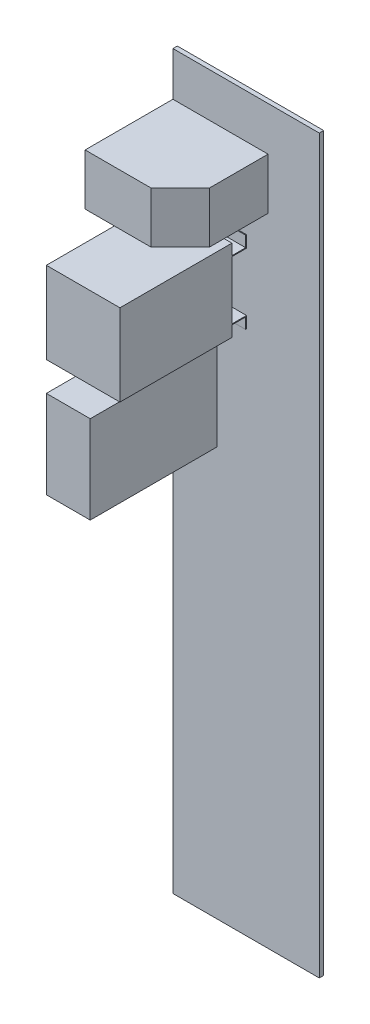
SolidWorks part; units mm, degrees
ref_plane "前视基准面" through (0, 0, 0) normal (0, 0, 1) x (1, 0, 0)
ref_plane "上视基准面" through (0, 0, 0) normal (0, 1, 0) x (1, 0, 0)
ref_plane "右视基准面" through (0, 0, 0) normal (1, 0, 0) x (0, 0, -1)
sketch "草图1" plane through (0, 0, 0) normal (0, 0, 1) x (1, 0, 0)
  line L1 (-251.5, 279) -> (251.5, 279)
  line L2 (-251.5, 279) -> (-251.5, -279)
  line L3 (-251.5, -279) -> (251.5, -279)
  line L4 (251.5, 279) -> (251.5, -279)
  line L5 (-251.5, 279) -> (251.5, -279) construction
  line L6 (-251.5, -279) -> (251.5, 279) construction
  point P0 (0, 0)
  dimension "D1" = 558
  dimension "D2" = 503
extrude "凸台-拉伸1" add sketch "草图1" along normal blind 865
sketch "草图2" plane through (251.5, 0, 0) normal (1, 0, 0) x (0, 0, -1)
  line L0 (0, -279) -> (0, 279) construction
  line L1 (100, 199) -> (-100, 199)
  line L2 (100, 199) -> (100, -199)
  line L3 (100, -199) -> (-100, -199)
  line L4 (-100, 199) -> (-100, -199)
  line L5 (100, 199) -> (-100, -199) construction
  line L6 (100, -199) -> (-100, 199) construction
  line L7 (-865, -279) -> (0, -279) construction
  point P0 (0, 0)
  dimension "D1" = 100
  dimension "D2" = 80
extrude "切除-拉伸1" cut sketch "草图2" against normal through all
sketch "草图3" plane through (251.5, 0, 0) normal (1, 0, 0) x (0, 0, -1)
  line L0 (-865, -279) -> (0, -279) construction
  line L1 (-100, -353) -> (-6, -353)
  line L2 (-100, -353) -> (-100, -205)
  line L3 (-100, -205) -> (-6, -205)
  line L4 (-6, -353) -> (-6, -205)
  line L5 (-100, -353) -> (-6, -205) construction
  line L6 (-100, -205) -> (-6, -353) construction
  line L7 (-100, 199) -> (-100, -199) construction
  line L8 (0, -279) -> (0, -199) construction
  line L9 (-100, -199) -> (0, -199) construction
  point P0 (-53, -279)
  dimension "D1" = 6
  dimension "D2" = 6
extrude "切除-拉伸2" cut sketch "草图3" against normal through all
mirror "镜向1" about plane through (0, 0, 0) normal (0, 1, 0) of "切除-拉伸2"
sketch "草图4" plane through (0, 0, 0) normal (0, 0, -1) x (-1, 0, 0)
  line L0 (251.5, -279) -> (-251.5, -279) construction
  line L1 (251.5, -479) -> (-48.5, -479)
  line L2 (251.5, -479) -> (251.5, -1079)
  line L3 (251.5, -1079) -> (-48.5, -1079)
  line L4 (-48.5, -479) -> (-48.5, -1079)
  dimension "D1" = 600
  dimension "D2" = 300
  dimension "D3" = 200
extrude "凸台-拉伸2" add sketch "草图4" against normal blind 865 separate body
sketch "草图5" plane through (0, 0, 0) normal (0, 0, -1) x (-1, 0, 0)
  line L0 (251.5, 279) -> (251.5, -279) construction
  line L1 (251.5, 479) -> (-398.5, 479)
  line L2 (251.5, 479) -> (251.5, 829)
  line L3 (251.5, 829) -> (-398.5, 829)
  line L4 (-398.5, 479) -> (-398.5, 829)
  line L5 (-251.5, 279) -> (251.5, 279) construction
  dimension "D1" = 650
  dimension "D2" = 350
  dimension "D3" = 200
extrude "凸台-拉伸3" add sketch "草图5" against normal blind 600 separate body
chamfer "倒角1" distance 200 angle 45 1 edges at (398.5, 654, 600)
sketch "草图6" plane through (0, 0, 0) normal (0, 0, -1) x (-1, 0, 0)
  line L0 (251.5, 479) -> (251.5, 829) construction
  line L1 (251.5, 1129) -> (-748.5, 1129)
  line L2 (251.5, 1129) -> (251.5, -3871)
  line L3 (251.5, -3871) -> (-748.5, -3871)
  line L4 (-748.5, 1129) -> (-748.5, -3871)
  line L5 (251.5, 829) -> (-398.5, 829) construction
  dimension "D1" = 300
  dimension "D2" = 1000
  dimension "D3" = 5000
extrude "凸台-拉伸4" add sketch "草图6" along normal blind 30 separate body
equation "\"零件重量\"= \"SW-质量\""
